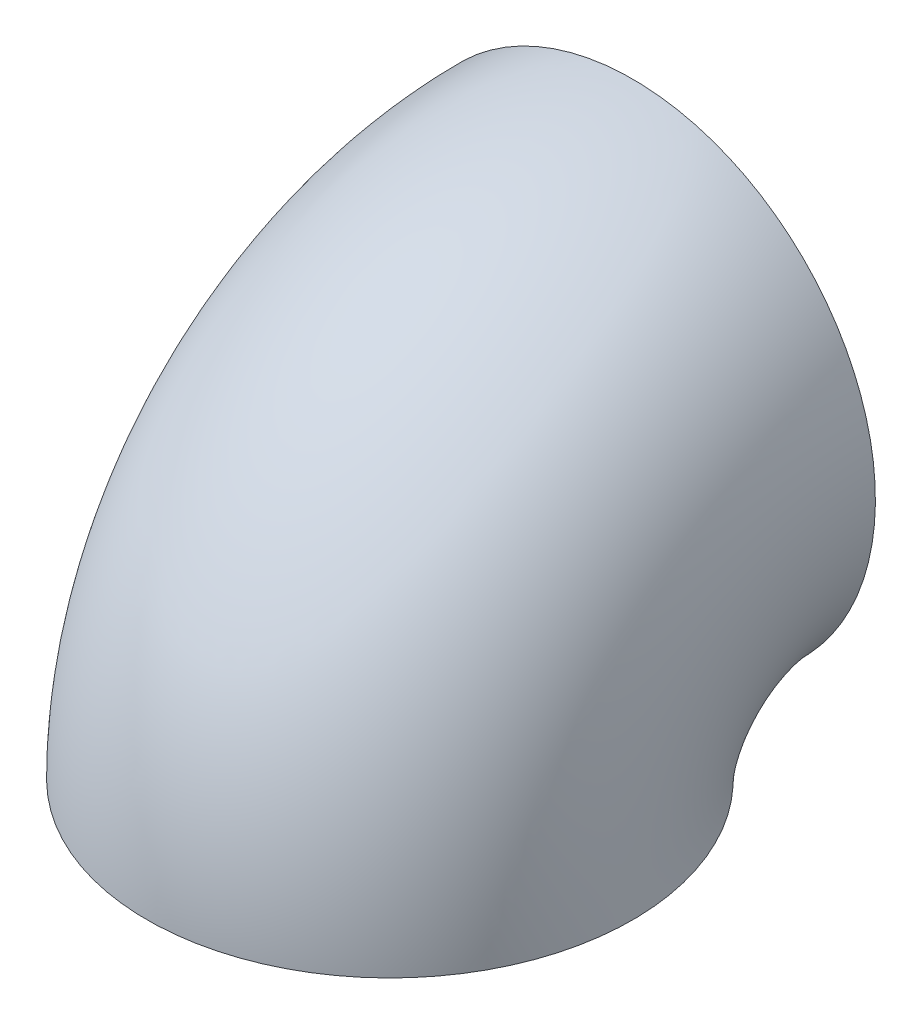
SolidWorks part; units mm, degrees
ref_plane "Front Plane" through (0, 0, 0) normal (0, 0, 1) x (1, 0, 0)
ref_plane "Top Plane" through (0, 0, 0) normal (0, 1, 0) x (1, 0, 0)
ref_plane "Right Plane" through (0, 0, 0) normal (1, 0, 0) x (0, 0, -1)
sketch "Sketch1" plane through (0, 0, 0) normal (1, 0, 0) x (0, 0, -1)
  arc A0 (0, 45) -> (-45, 0) centre (0, 0) ccw
  dimension "D1" = 45
sketch "Sketch2" plane through (0, 0, 0) normal (0, 1, 0) x (1, 0, 0)
  line L0 (0, -45) -> (0, 0) construction
  circle A0 centre (0, -45) radius 45
  circle A1 centre (0, -45) radius 10
  dimension "D1" = 90
  dimension "D2" = 20
sweep "Sweep1" add profiles "Sketch2" path "Sketch1"
ref_point "Point1"
sketch "Sketch3" plane through (0, 0, 0) normal (0, 0, -1) x (-1, 0, 0)
  line L0 (0, 45) -> (65.535, 45) construction
  line L1 (65.535, 45) -> (65.535, 16.4489) construction
